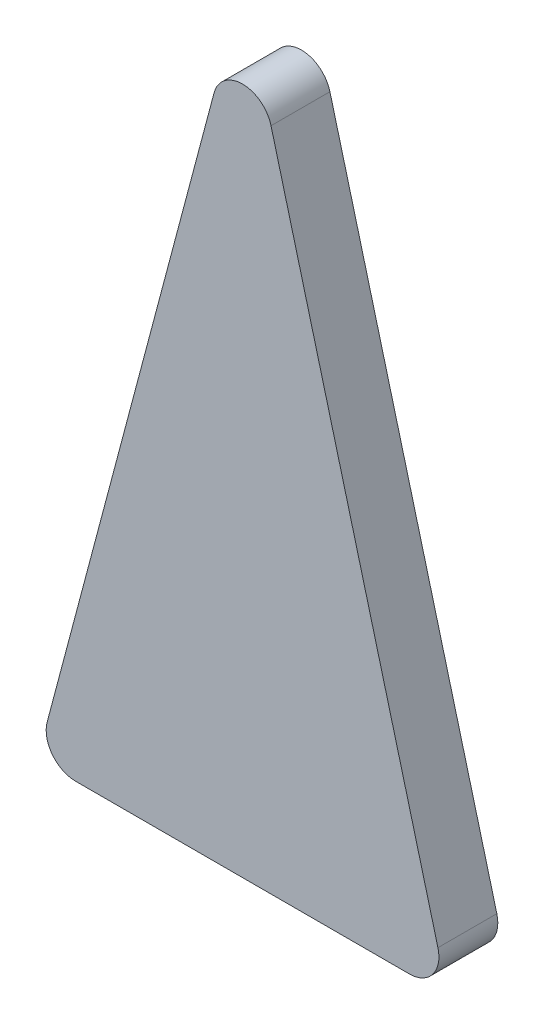
SolidWorks part; units mm, degrees
material "Plain Carbon Steel"
ref_plane "Спереди" through (0, 0, 0) normal (0, 0, 1) x (1, 0, 0)
ref_plane "Сверху" through (0, 0, 0) normal (0, 1, 0) x (1, 0, 0)
ref_plane "Справа" through (0, 0, 0) normal (1, 0, 0) x (0, 0, -1)
sketch "Sketch1" plane through (0, 0, 0) normal (0, 0, 1) x (1, 0, 0)
  line L0 (0, 0) -> (0, 62.5556) construction
  line L1 (-17, 0) -> (17, 0)
  line L2 (19.8995, 3.7702) -> (2.8995, 67.7702)
  line L3 (-19.8995, 3.7702) -> (-2.8995, 67.7702)
  arc A0 (-19.8995, 3.7702) -> (-17, 0) centre (-17, 3) ccw
  arc A1 (2.8995, 67.7702) -> (-2.8995, 67.7702) centre (0, 67) ccw
  arc A2 (17, 0) -> (19.8995, 3.7702) centre (17, 3) ccw
  point P8 (-20.9009, 0)
  point P11 (0, 78.6858)
  point P14 (20.9009, 0)
  dimension "D1" = 3
  dimension "D2" = 40
  dimension "D3" = 70
extrude "Extrude1" add sketch "Sketch1" along normal blind 6
